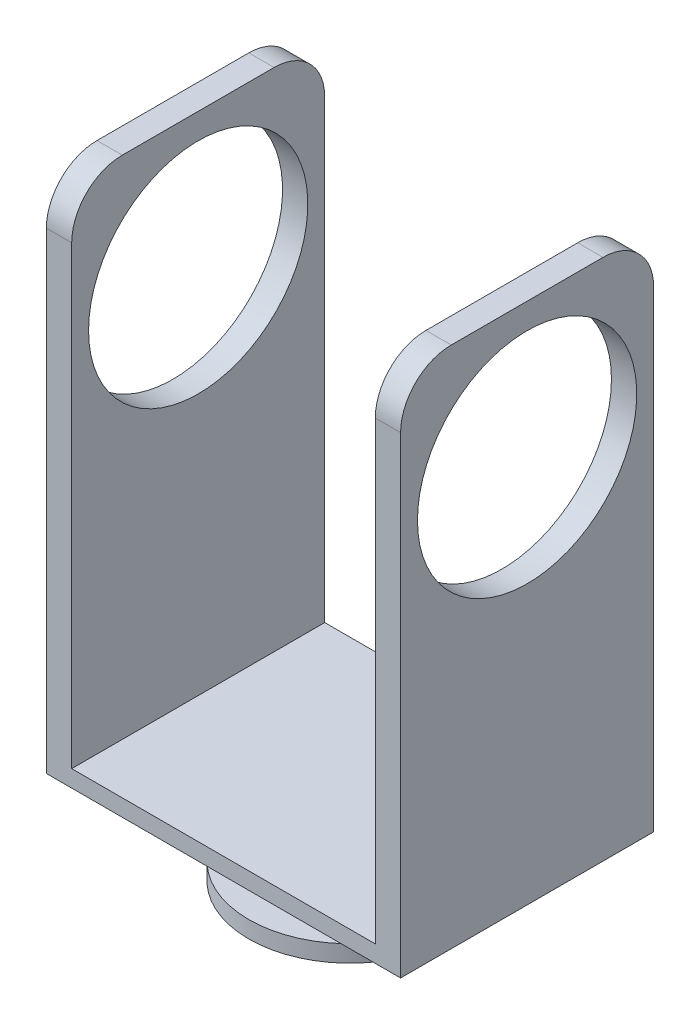
SolidWorks part; units mm, degrees
ref_plane "Alzado" through (0, 0, 0) normal (0, 0, 1) x (1, 0, 0)
ref_plane "Planta" through (0, 0, 0) normal (0, 1, 0) x (1, 0, 0)
ref_plane "Vista lateral" through (0, 0, 0) normal (1, 0, 0) x (0, 0, -1)
sketch "Croquis1" plane through (0, 0, 0) normal (0, 1, 0) x (1, 0, 0)
  circle A0 centre (0, 0) radius 6
extrude "Saliente-Extruir1" add sketch "Croquis1" along normal blind 1
sketch "Croquis2" plane through (0, 1, 0) normal (0, 1, 0) x (1, 0, 0)
  circle A0 centre (0, 0) radius 2.5
extrude "Saliente-Extruir2" add sketch "Croquis2" along normal blind 3
sketch "Croquis3" plane through (0, 4, 0) normal (0, 1, 0) x (1, 0, 0)
  line L1 (-10.5, 7.5) -> (10.5, 7.5)
  line L2 (-10.5, 7.5) -> (-10.5, -7.5)
  line L3 (-10.5, -7.5) -> (10.5, -7.5)
  line L4 (10.5, 7.5) -> (10.5, -7.5)
  line L5 (0, -7.5) -> (0, 7.5) construction
  line L6 (-10.5, 0) -> (10.5, 0) construction
  point P0 (0, 0)
  dimension "D1" = 15
  dimension "D2" = 21
extrude "Saliente-Extruir3" add sketch "Croquis3" along normal blind 1
sketch "Croquis4" plane through (0, 5, 0) normal (0, 1, 0) x (1, 0, 0)
  line L0 (-10.5, -7.5) -> (10.5, -7.5) construction
  line L1 (-10.5, 7.5) -> (-9, 7.5)
  line L2 (-10.5, 7.5) -> (-10.5, -7.5)
  line L3 (-10.5, -7.5) -> (-9, -7.5)
  line L4 (-9, 7.5) -> (-9, -7.5)
  line L6 (10.5, 7.5) -> (9, 7.5)
  line L7 (10.5, 7.5) -> (10.5, -7.5)
  line L8 (10.5, -7.5) -> (9, -7.5)
  line L9 (9, 7.5) -> (9, -7.5)
  dimension "D1" = 1.5
  dimension "D2" = 1.5
extrude "Saliente-Extruir4" add sketch "Croquis4" along normal blind 30
sketch "Croquis5" plane through (-10.5, 0, 0) normal (-1, 0, 0) x (0, 0, 1)
  circle A0 centre (0, 26.9884) radius 6.5
  point P0 (0, 26.9884)
  dimension "D2" = 13
extrude "Cortar-Extruir1" cut sketch "Croquis5" against normal blind 34
fillet "Redondeo1" radius 3 4 edges at (9.75, 35, 7.5) (9.75, 35, -7.5) (-9.75, 35, 7.5) (-9.75, 35, -7.5)
